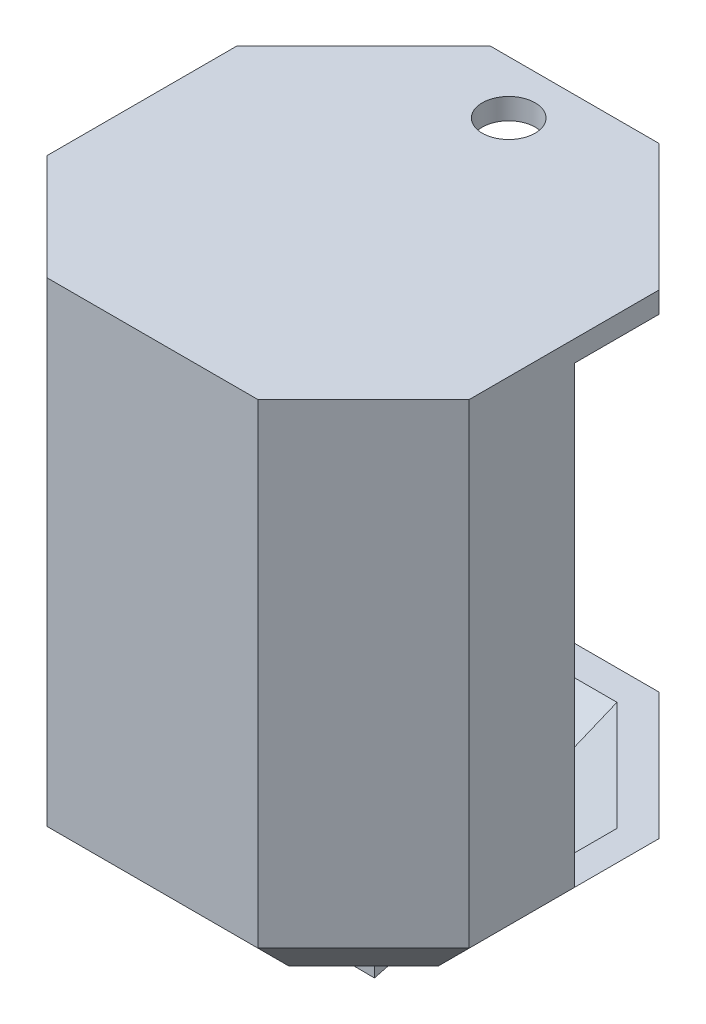
SolidWorks part; units mm, degrees
ref_plane "Front Plane" through (0, 0, 0) normal (0, 0, 1) x (1, 0, 0)
ref_plane "Top Plane" through (0, 0, 0) normal (0, 1, 0) x (1, 0, 0)
ref_plane "Right Plane" through (0, 0, 0) normal (1, 0, 0) x (0, 0, -1)
sketch "Sketch1" plane through (0, 0, 0) normal (0, 0, 1) x (1, 0, 0)
  line L1 (-20, -25) -> (20, -25)
  line L2 (-20, -25) -> (-20, 25)
  line L3 (-20, 25) -> (20, 25)
  line L4 (20, -25) -> (20, 25)
  line L5 (-20, -25) -> (20, 25) construction
  line L6 (-20, 25) -> (20, -25) construction
  point P0 (0, 0)
  dimension "D1" = 40
  dimension "D2" = 50
extrude "Boss-Extrude1" add sketch "Sketch1" along normal blind 40
chamfer "Chamfer1" distance 10 angle 45 2 edges at (20, 0, 40) (-20, 0, 40)
chamfer "Chamfer2" distance 12 angle 45 2 edges at (20, 0, 0) (-20, 0, 0)
chamfer "Chamfer4" distance 5 angle 45 8 edges at (-15, -25, 35) (0, -25, 40) (15, -25, 35) (20, -25, 21) (14, -25, 6) (0, -25, 0) (-14, -25, 6) (-20, -25, 21)
sketch "Sketch2" plane through (0, -25, 0) normal (0, -1, 0) x (1, 0, 0)
  line L0 (6.2721, 31) -> (-6.2721, 31)
  line L1 (-6.2721, 31) -> (-11, 26.2721)
  line L2 (-11, 26.2721) -> (-11, 15.7279)
  line L3 (-11, 15.7279) -> (-4.2721, 9)
  line L4 (-4.2721, 9) -> (4.2721, 9)
  line L5 (4.2721, 9) -> (11, 15.7279)
  line L6 (11, 15.7279) -> (11, 26.2721)
  line L7 (11, 26.2721) -> (6.2721, 31)
  line L8 (7.9289, 35) -> (-7.9289, 35)
  line L9 (-7.9289, 35) -> (-15, 27.9289)
  line L10 (-15, 27.9289) -> (-15, 14.0711)
  line L11 (-15, 14.0711) -> (-5.9289, 5)
  line L12 (-5.9289, 5) -> (5.9289, 5)
  line L13 (5.9289, 5) -> (15, 14.0711)
  line L14 (15, 14.0711) -> (15, 27.9289)
  line L15 (15, 27.9289) -> (7.9289, 35)
  line L16 (7.9289, 35) -> (-7.9289, 35)
  line L17 (-7.9289, 35) -> (-15, 27.9289)
  line L18 (-15, 27.9289) -> (-15, 14.0711)
  line L19 (-15, 14.0711) -> (-5.9289, 5)
  line L20 (-5.9289, 5) -> (5.9289, 5)
  line L21 (5.9289, 5) -> (15, 14.0711)
  line L22 (15, 14.0711) -> (15, 27.9289)
  line L23 (15, 27.9289) -> (7.9289, 35)
  dimension "D1" = 0
  dimension "D2" = 4
extrude "Boss-Extrude2" add sketch "Sketch2" along normal blind 4 contours L0 L1 L2 L3 L4 L5 L6 L7
chamfer "Chamfer5" distance 2 angle 45 8 edges at (11, -29, 21) (7.636, -29, 12.364) (0, -29, 9) (-7.636, -29, 12.364) (-11, -29, 21) (-8.636, -29, 28.636) (0, -29, 31) (8.636, -29, 28.636)
shell "Shell1" thickness 2
sketch "Sketch3" plane through (0, 0, 0) normal (0, 0, -1) x (-1, 0, 0)
  line L0 (20, 25) -> (20, -20) construction
  line L1 (-25, -20) -> (20, -20)
  line L2 (-25, -20) -> (-25, 23)
  line L3 (-25, 23) -> (20, 23)
  line L4 (20, -20) -> (20, 23)
  line L5 (-8, -20) -> (8, -20) construction
  dimension "D1" = 45
  dimension "D2" = 43
  dimension "D3" = 0
extrude "Cut-Extrude1" cut sketch "Sketch3" against normal blind 20
sketch "Sketch4" plane through (0, 23, 0) normal (0, -1, 0) x (1, 0, 0)
  line L0 (8, 0) -> (-8, 0) construction
  circle A0 centre (-1.2227, 5.0309) radius 2.5
  dimension "D1" = 5
  dimension "D2" = 5.0309
  dimension "D3" = 6.7773
extrude "Cut-Extrude2" cut sketch "Sketch4" against normal blind 10 and the other way through all
sketch "Sketch5" plane through (0, -29, 0) normal (0, -1, 0) x (1, 0, 0)
  line L0 (26.5213, 125.3363) -> (171.1879, 125.3363) construction
  line L1 (-3.908, 25.8734) -> (-1.8522, 26.5786)
  line L2 (-1.8522, 26.5786) -> (2.1624, 26.5786)
  line L3 (2.1624, 26.5786) -> (4.2063, 25.8396)
  line L4 (4.2063, 25.8396) -> (4.1831, 24.5135)
  line L5 (4.1831, 24.5135) -> (0.1741, 21.9251)
  line L6 (0.1741, 21.9251) -> (-3.7038, 24.5665)
  line L7 (-3.7038, 24.5665) -> (-3.908, 25.8734)
  line L8 (-6.6405, 25.8734) -> (-4.2224, 25.8734)
  line L9 (-4.2224, 25.8734) -> (-3.9906, 24.3901)
  line L10 (-3.9906, 24.3901) -> (-1.4529, 22.6615)
  line L11 (-1.4529, 22.6615) -> (-1.0085, 19.8174)
  line L12 (-1.0085, 19.8174) -> (-3.7863, 20.2579)
  line L13 (-3.7863, 20.2579) -> (-5.7466, 21.6464)
  line L14 (-5.7466, 21.6464) -> (-6.6405, 25.8734)
  line L15 (0.1755, 21.5791) -> (-1.1949, 22.5126)
  line L16 (-1.1949, 22.5126) -> (-0.7542, 19.6923)
  line L17 (-0.7542, 19.6923) -> (-0.7542, 16.3369)
  line L18 (-0.7542, 16.3369) -> (1.148, 16.3369)
  line L19 (1.148, 16.3369) -> (1.148, 19.6551)
  line L20 (1.148, 19.6551) -> (1.5685, 22.4785)
  line L21 (1.5685, 22.4785) -> (0.1755, 21.5791)
  line L22 (-1.2679, 24.8289) -> (1.6873, 24.8289)
  line L23 (1.6873, 24.8289) -> (1.6873, 24.5845)
  line L24 (1.6873, 24.5845) -> (0.1673, 23.6031)
  line L25 (0.1673, 23.6031) -> (-1.2679, 24.5807)
  line L26 (-1.2679, 24.5807) -> (-1.2679, 24.8289)
  line L27 (-5.3719, 21.1029) -> (-5.0404, 15.8727)
  line L28 (-5.0404, 15.8727) -> (-2.9187, 14.004)
  line L29 (-2.9187, 14.004) -> (-2.9187, 18.8833)
  line L30 (-2.9187, 18.8833) -> (-3.8976, 19.3636)
  line L31 (-3.8976, 19.3636) -> (-3.8976, 20.0519)
  line L32 (-3.8976, 20.0519) -> (-5.3719, 21.1029)
  line L33 (-2.5778, 18.6383) -> (-2.5778, 13.83)
  line L34 (-2.5778, 13.83) -> (-1.7879, 13.1343)
  line L35 (-1.7879, 13.1343) -> (-0.9481, 15.1715)
  line L36 (-0.9481, 15.1715) -> (1.4462, 15.1715)
  line L37 (1.4462, 15.1715) -> (2.1404, 13.1318)
  line L38 (2.1404, 13.1318) -> (2.9585, 13.7271)
  line L39 (2.9585, 13.7271) -> (2.9585, 18.5818)
  line L40 (2.9585, 18.5818) -> (1.348, 19.2457)
  line L41 (1.348, 19.2457) -> (1.348, 16.1369)
  line L42 (1.348, 16.1369) -> (-0.9542, 16.1369)
  line L43 (-0.9542, 16.1369) -> (-0.9542, 19.3219)
  line L44 (-0.9542, 19.3219) -> (-2.5778, 18.6383)
  line L45 (-1.4522, 13.1318) -> (1.8722, 13.1318)
  line L46 (1.8722, 13.1318) -> (1.2258, 14.8674)
  line L47 (1.2258, 14.8674) -> (-0.8226, 14.8674)
  line L48 (-0.8226, 14.8674) -> (-1.4522, 13.1318)
  line L49 (-5.1797, 24.2639) -> (-5.1797, 23.8101)
  line L50 (-5.1797, 23.8101) -> (-2.3712, 21.9248)
  line L51 (-2.3712, 21.9248) -> (-2.3712, 22.4268)
  line L52 (-2.3712, 22.4268) -> (-5.1797, 24.2639)
  line L53 (-4.9742, 23.0566) -> (-4.9742, 22.6847)
  line L54 (-4.9742, 22.6847) -> (-2.1753, 20.8059)
  line L55 (-2.1753, 20.8059) -> (-2.1753, 21.1679)
  line L56 (-2.1753, 21.1679) -> (-4.9742, 23.0566)
  line L57 (0.1551, 26.5786) -> (0.21, 13.1318) construction
  line L58 (9, 16.5563) -> (9, 25.4437) construction
  line L60 (5.4437, 29) -> (-5.4437, 29) construction
  line L61 (2.7194, 21.9456) -> (2.7153, 22.4476)
  line L62 (5.5124, 23.8537) -> (2.7194, 21.9456)
  line L63 (5.5087, 24.3075) -> (5.5124, 23.8537)
  line L64 (2.7153, 22.4476) -> (5.5087, 24.3075)
  line L65 (2.5326, 20.8251) -> (2.5297, 21.1871)
  line L66 (5.3161, 22.7267) -> (2.5326, 20.8251)
  line L67 (5.313, 23.0985) -> (5.3161, 22.7267)
  line L68 (2.5297, 21.1871) -> (5.313, 23.0985)
  line L69 (4.148, 20.2903) -> (6.0969, 21.6947)
  line L70 (1.3739, 19.8271) -> (4.148, 20.2903)
  line L71 (1.7951, 22.6748) -> (1.3739, 19.8271)
  line L72 (4.3186, 24.424) -> (1.7951, 22.6748)
  line L73 (4.5383, 25.9092) -> (4.3186, 24.424)
  line L74 (6.9562, 25.9289) -> (4.5383, 25.9092)
  line L75 (6.0969, 21.6947) -> (6.9562, 25.9289)
  line L76 (4.2665, 19.3969) -> (4.2609, 20.0852)
  line L77 (3.2916, 18.9087) -> (4.2665, 19.3969)
  line L78 (3.3314, 14.0295) -> (3.2916, 18.9087)
  line L79 (5.4378, 15.9155) -> (3.3314, 14.0295)
  line L80 (5.7267, 21.1482) -> (5.4378, 15.9155)
  line L81 (4.2609, 20.0852) -> (5.7267, 21.1482)
  point P63 (0.1969, 16.3369)
  dimension "D1" = 0.2
  dimension "D2" = 0.2
  dimension "D3" = 0.2
  dimension "D4" = 4.7937
  dimension "D5" = 4.8169
  dimension "D6" = 6.0415
  dimension "D7" = 6.8376
  dimension "D8" = 6.8596
  dimension "D9" = 7.1278
  dimension "D10" = 7.3127
  dimension "D11" = 7.4315
  dimension "D12" = 7.5538
  dimension "D13" = 7.652
  dimension "D14" = 7.7742
  dimension "D15" = 8.8031
  dimension "D16" = 8.8245
  dimension "D17" = 8.8259
  dimension "D18" = 8.8327
  dimension "D19" = 9.8226
  dimension "D20" = 9.9481
  dimension "D21" = 10.0085
  dimension "D22" = 10.1949
  dimension "D23" = 10.2679
  dimension "D24" = 10.4522
  dimension "D25" = 10.4529
  dimension "D26" = 10.7879
  dimension "D27" = 10.8522
  dimension "D28" = 11.1753
  dimension "D29" = 11.3712
  dimension "D30" = 11.5778
  dimension "D31" = 11.9187
  dimension "D32" = 12.7038
  dimension "D33" = 12.7863
  dimension "D34" = 12.8976
  dimension "D35" = 12.908
  dimension "D36" = 12.9906
  dimension "D37" = 13.2224
  dimension "D38" = 13.9742
  dimension "D39" = 14.0404
  dimension "D40" = 14.1797
  dimension "D41" = 14.3719
  dimension "D42" = 14.7466
  dimension "D43" = 15.6405
  dimension "D44" = 96.3363
  dimension "D45" = 96.3363
  dimension "D46" = 2.4214
  dimension "D47" = 3.1266
  dimension "D48" = 4.1711
  dimension "D49" = 4.4155
  dimension "D50" = 4.4193
  dimension "D51" = 4.7361
  dimension "D52" = 5.1899
  dimension "D53" = 5.9434
  dimension "D54" = 6.3153
  dimension "D55" = 6.5732
  dimension "D56" = 7.0752
  dimension "D57" = 7.3536
  dimension "D58" = 7.8321
  dimension "D59" = 7.8971
  dimension "D60" = 8.7421
  dimension "D61" = 8.9481
  dimension "D62" = 9.6364
  dimension "D63" = 9.6781
  dimension "D64" = 9.7543
  dimension "D65" = 10.1167
  dimension "D66" = 10.3617
  dimension "D67" = 10.4182
  dimension "D68" = 13.1273
  dimension "D69" = 13.8285
  dimension "D70" = 14.1326
  dimension "D71" = 14.996
  dimension "D72" = 15.2729
extrude "Boss-Extrude3" add sketch "Sketch5" along normal blind 2
